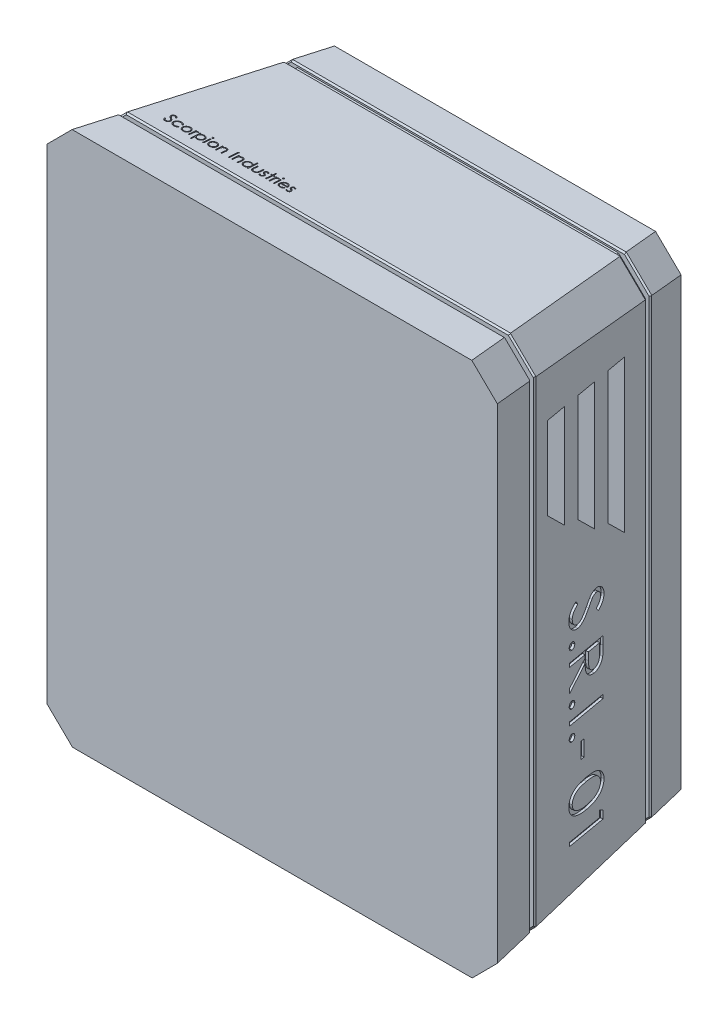
SolidWorks part; units mm, degrees
ref_plane "Front Plane" through (0, 0, 0) normal (0, 0, 1) x (1, 0, 0)
ref_plane "Top Plane" through (0, 0, 0) normal (0, 1, 0) x (1, 0, 0)
ref_plane "Right Plane" through (0, 0, 0) normal (1, 0, 0) x (0, 0, -1)
sketch "Sketch1" plane through (0, 0, 0) normal (0, 0, 1) x (1, 0, 0)
  line L1 (57.15, -76.2) -> (-57.15, -76.2)
  line L2 (57.15, -76.2) -> (57.15, 76.2)
  line L3 (57.15, 76.2) -> (-57.15, 76.2)
  line L4 (-57.15, -76.2) -> (-57.15, 76.2)
  line L5 (57.15, -76.2) -> (-57.15, 76.2) construction
  line L6 (57.15, 76.2) -> (-57.15, -76.2) construction
  point P0 (0, 0)
  dimension "D1" = 114.3
  dimension "D2" = 152.4
extrude "Extrude-Thin1" add sketch "Sketch1" along normal blind 68.58 thin
sketch "Sketch2" plane through (0, 0, 68.58) normal (0, 0, 1) x (1, 0, 0)
  line L1 (57.15, -76.2) -> (-57.15, -76.2)
  line L2 (57.15, -76.2) -> (57.15, 76.2)
  line L3 (57.15, 76.2) -> (-57.15, 76.2)
  line L4 (-57.15, -76.2) -> (-57.15, 76.2)
  line L5 (57.15, -76.2) -> (-57.15, 76.2) construction
  line L6 (57.15, 76.2) -> (-57.15, -76.2) construction
  point P0 (0, 0)
extrude "Boss-Extrude1" add sketch "Sketch2" against normal blind 6.35
sketch "Sketch3" plane through (0, 0, 62.23) normal (0, 0, -1) x (-1, 0, 0)
  circle A0 centre (0, -20.32) radius 44.45 construction
  circle A1 centre (0, -20.32) radius 14.5415
  dimension "D1" = 88.9
  dimension "D2" = 29.083
  dimension "D3" = 20.32
extrude "Extrude-Thin2" add sketch "Sketch3" along normal blind 49.53 thin
sketch "Sketch4" plane through (0, 0, 62.23) normal (0, 0, -1) x (-1, 0, 0)
  line L1 (20.955, 15.367) -> (-20.955, 15.367)
  line L2 (20.955, 15.367) -> (20.955, 57.277)
  line L3 (20.955, 57.277) -> (-20.955, 57.277)
  line L4 (-20.955, 15.367) -> (-20.955, 57.277)
  line L5 (20.955, 15.367) -> (-20.955, 57.277) construction
  line L6 (20.955, 57.277) -> (-20.955, 15.367) construction
  point P0 (0, 36.322)
  dimension "D1" = 41.91
  dimension "D2" = 36.322
extrude "Cut-Extrude1" cut sketch "Sketch4" against normal blind 3.81
sketch "Sketch5" plane through (0, 0, 0) normal (0, 0, -1) x (-1, 0, 0)
  line L8 (44.45, -73.025) -> (-44.45, -73.025) construction
  line L9 (44.45, -73.025) -> (44.45, 73.025) construction
  line L10 (44.45, 73.025) -> (-44.45, 73.025) construction
  line L11 (-44.45, -73.025) -> (-44.45, 73.025) construction
  line L12 (44.45, -73.025) -> (-44.45, 73.025) construction
  line L13 (44.45, 73.025) -> (-44.45, -73.025) construction
  circle A0 centre (-44.45, 73.025) radius 1.397
  circle A1 centre (44.45, 73.025) radius 1.397
  circle A2 centre (44.45, -73.025) radius 1.397
  circle A3 centre (-44.45, -73.025) radius 1.397
  point P0 (0, 0)
  point P6 (0, 0)
  dimension "D3" = 2.794
  dimension "D1" = 146.05
  dimension "D2" = 88.9
extrude "Cut-Extrude2" cut sketch "Sketch5" against normal blind 6.35
ref_plane "Plane2" through (0, 0, 11.43) normal (0, 0, -1) x (-1, 0, 0)
draft "Draft4" type of draft neutral plane draft angle 10 faces to draft 2 face at (57.15, 0, 34.29) face at (-57.15, 0, 34.29) neutral plane through (0, 0, 0) neutral plane normal (0, 0, -1) parameters "D1"=10
draft "Draft5" type of draft neutral plane draft angle 5 faces to draft 2 face at (0, 76.2, 34.29) face at (0, -76.2, 34.29) neutral plane through (0, 0, 0) neutral plane normal (0, 0, -1) parameters "D1"=5
chamfer "Chamfer2" distance 7.62 angle 45 4 edges at (63.1963, 79.2, 34.29) (-63.1963, 79.2, 34.29) (63.1963, -79.2, 34.29) (-63.1963, -79.2, 34.29)
sketch "Sketch9" plane through (0, 0, 11.43) normal (0, 0, -1) x (-1, 0, 0)
  line L0 (-57.15, 68.5518) -> (-49.2935, 76.2)
  line L1 (-49.2935, 76.2) -> (49.4133, 76.2)
  line L2 (49.4133, 76.2) -> (57.15, 68.4333)
  line L3 (57.15, 68.4333) -> (57.15, -68.5518)
  line L4 (57.15, -68.5518) -> (49.2935, -76.2)
  line L5 (49.2935, -76.2) -> (-49.4133, -76.2)
  line L6 (-49.4133, -76.2) -> (-57.15, -68.4333)
  line L7 (-57.15, -68.4333) -> (-57.15, 68.5518)
extrude "Cut-Extrude-Thin4" cut sketch "Sketch9" against normal blind 1.27 thin thin type one direction wall 5.08
chamfer "Chamfer3" distance 0.508 angle 45 16 edges at (55.2971, -73.3167, 11.43) (59.1654, 0.0592, 11.43) (55.2372, 73.3759, 11.43) (-0.0599, 77.2, 11.43) (-55.2971, 73.3167, 11.43) (0.0599, -77.2, 11.43) (-55.2372, -73.3759, 11.43) (-59.1654, -0.0592, 11.43) (-55.4611, -73.487, 12.7) (-59.3894, -0.0592, 12.7) (-55.521, 73.4278, 12.7) (-0.0599, 77.3111, 12.7) (55.4611, 73.487, 12.7) (59.3894, 0.0592, 12.7) (0.0599, -77.3111, 12.7) (55.521, -73.4278, 12.7)
ref_plane "Plane3" through (0, 0, 55.88) normal (0, 0, 1) x (1, 0, 0)
sketch "Sketch11" plane through (0, 0, 55.88) normal (0, 0, 1) x (1, 0, 0)
  line L0 (-69.2425, 74.4333) -> (-61.5058, 82.2)
  line L1 (-61.5058, 82.2) -> (61.386, 82.2)
  line L2 (61.386, 82.2) -> (69.2425, 74.5517)
  line L3 (69.2425, 74.5517) -> (69.2425, -74.4333)
  line L4 (69.2425, -74.4333) -> (61.5058, -82.2)
  line L5 (61.5058, -82.2) -> (-61.386, -82.2)
  line L6 (-61.386, -82.2) -> (-69.2425, -74.5517)
  line L7 (-69.2425, -74.5517) -> (-69.2425, 74.4333)
extrude "Cut-Extrude-Thin6" cut sketch "Sketch11" against normal blind 1.27 thin
chamfer "Chamfer4" distance 0.508 angle 45 16 edges at (-63.1348, 77.2055, 55.88) (-62.9109, 77.0944, 54.61) (-0.0599, 80.9778, 54.61) (-0.0599, 81.0889, 55.88) (63.0749, 77.2648, 55.88) (62.851, 77.1536, 54.61) (67.0032, 0.0592, 55.88) (66.7792, 0.0592, 54.61) (62.9109, -77.0944, 54.61) (63.1348, -77.2055, 55.88) (-66.7792, -0.0592, 54.61) (-62.851, -77.1536, 54.61) (0.0599, -80.9778, 54.61) (0.0599, -81.0889, 55.88) (-67.0032, -0.0592, 55.88) (-63.0749, -77.2648, 55.88)
sketch "Sketch14" plane through (55.4267, 0, -9.7732) normal (0.9848, 0, -0.1736) x (-0.1736, 0, -0.9848)
  line L0 (-52.1684, 72.1915) -> (-52.1684, -72.0731) construction
  line L1 (-23.4534, 69.7175) -> (-64.8684, 73.2858) construction
  line L2 (-64.8684, -73.1673) -> (-23.4541, -69.5991) construction
  line L4 (-64.8684, 73.2858) -> (-64.8684, -73.1673) construction
  text T0 "            S.R.I.- 01" font "Century Gothic" height 12.7
  dimension "D1" = 12.7
extrude "Cut-Extrude6" cut sketch "Sketch14" against normal blind 0.762
sketch "Sketch15" plane through (55.4267, 0, -9.7732) normal (0.9848, 0, -0.1736) x (-0.1736, 0, -0.9848)
  line L0 (-37.652, 18.4579) -> (-31.302, 12.2795)
  line L1 (-42.732, 26.0779) -> (-49.082, 26.0779) construction
  line L2 (-42.732, 26.0779) -> (-42.732, 59.0979)
  line L3 (-42.732, 59.0979) -> (-49.082, 59.0979)
  line L4 (-49.082, 26.0779) -> (-49.082, 59.0979)
  line L5 (-42.732, 26.0779) -> (-49.082, 59.0979) construction
  line L6 (-42.732, 59.0979) -> (-49.082, 26.0779) construction
  line L7 (-54.162, 33.6979) -> (-60.512, 33.6979) construction
  line L8 (-54.162, 33.6979) -> (-54.162, 59.0979)
  line L9 (-54.162, 59.0979) -> (-60.512, 59.0979)
  line L10 (-60.512, 33.6979) -> (-60.512, 59.0979)
  line L11 (-54.162, 33.6979) -> (-60.512, 59.0979) construction
  line L12 (-54.162, 59.0979) -> (-60.512, 33.6979) construction
  line L13 (-31.302, 18.4579) -> (-37.652, 18.4579) construction
  line L14 (-31.302, 18.4579) -> (-31.302, 59.0979)
  line L15 (-31.302, 59.0979) -> (-37.652, 59.0979)
  line L16 (-37.652, 18.4579) -> (-37.652, 59.0979)
  line L17 (-31.302, 18.4579) -> (-37.652, 59.0979) construction
  line L18 (-31.302, 59.0979) -> (-37.652, 18.4579) construction
  line L19 (-31.302, 12.2795) -> (-31.302, 18.4579)
  line L20 (-49.082, 26.0779) -> (-42.732, 19.8995)
  line L21 (-42.732, 19.8995) -> (-42.732, 26.0779)
  line L22 (-60.512, 33.6979) -> (-54.162, 27.5195)
  line L23 (-54.162, 27.5195) -> (-54.162, 33.6979)
  line L25 (-79.562, -74.4333) -> (-79.562, 74.5517) construction
  line L28 (-52.1684, -25.9921) -> (-39.4684, -25.9921) construction
  point P0 (-45.907, 42.5879)
  point P5 (-57.337, 46.3979)
  point P10 (-34.477, 38.7779)
  dimension "D1" = 6.35
  dimension "D2" = 5.08
  dimension "D3" = 5.08
  dimension "D4" = 19.05
  dimension "D5" = 40.64
  dimension "D6" = 33.02
  dimension "D7" = 25.4
  dimension "D8" = 44.45
extrude "Cut-Extrude7" cut sketch "Sketch15" against normal blind 16.51
sketch "Sketch16" plane through (0, -75.6212, -6.616) normal (0, -0.9962, -0.0872) x (1, 0, 0)
  line L0 (-61.386, 75.4832) -> (61.5058, 75.4832) construction
  line L1 (22.225, 57.7032) -> (-22.225, 57.7032)
  line L2 (22.225, 57.7032) -> (22.225, 66.5932)
  line L3 (22.225, 66.5932) -> (-22.225, 66.5932)
  line L4 (-22.225, 57.7032) -> (-22.225, 66.5932)
  line L5 (22.225, 57.7032) -> (-22.225, 66.5932) construction
  line L6 (22.225, 66.5932) -> (-22.225, 57.7032) construction
  point P0 (0, 62.1482)
  dimension "D1" = 8.89
  dimension "D2" = 44.45
  dimension "D3" = 8.89
extrude "Cut-Extrude8" cut sketch "Sketch16" against normal blind 16.51
sketch "Sketch17" plane through (0, 75.6212, -6.616) normal (0, 0.9962, -0.0872) x (1, 0, 0)
  line L0 (-58.2841, -57.1419) -> (-10.6144, -57.1419) construction
  line L1 (-51.7628, -20.0168) -> (-58.9533, -60.9519) construction
  line L2 (-58.9533, -60.9519) -> (58.8335, -60.9519) construction
  text T0 "     Scorpion Industries"
  dimension "D1" = 3.81
extrude "Cut-Extrude9" cut sketch "Sketch17" against normal blind 0.762
